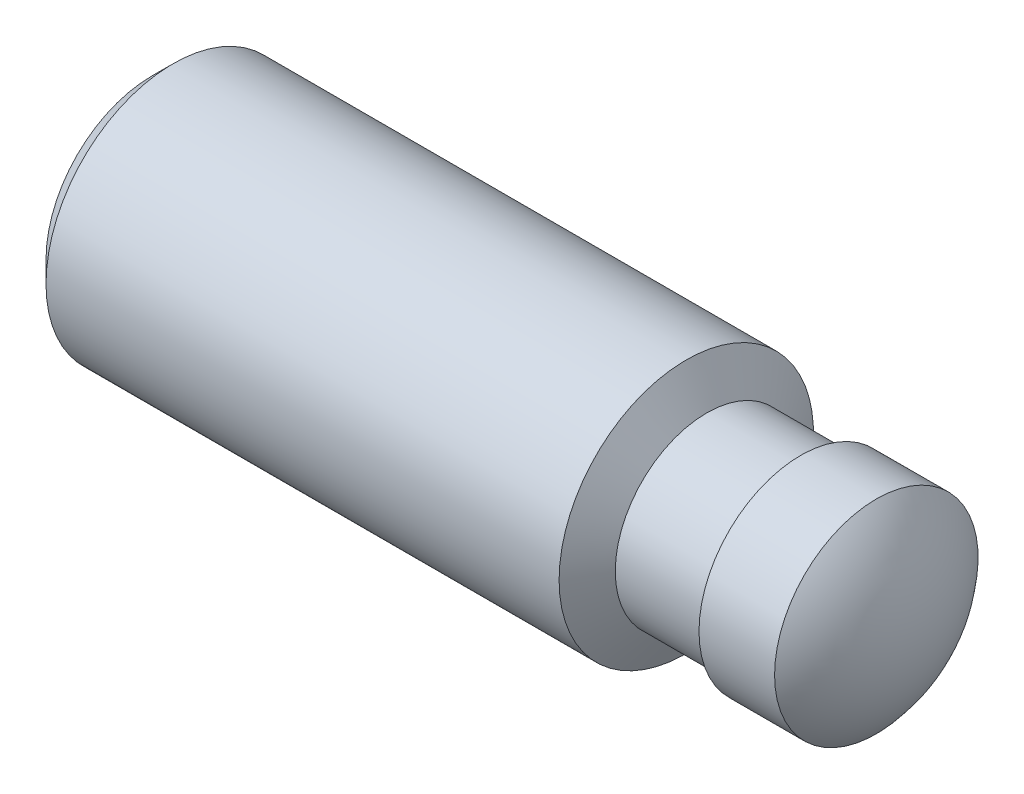
SolidWorks part; units mm, degrees
revolve "BaseBody" add sketch "BodySke" angle 360 about L5
sketch "BodySke" plane through (0, 0, 0) normal (0, 0, 1) x (1, 0, 0)
  line L0 (0.828, -5) -> (19.05, -5) construction
  line L1 (21.8083, 3.6) -> (25.5, 3.6)
  line L2 (0.828, 5) -> (21, 5)
  line L3 (21.8083, 3.6) -> (21, 5)
  line L5 (-3.175, 0) -> (33.7104, 0) construction
  line L6 (1.5, 12.7) -> (1.5, -6.35) construction
  line L7 (25.5, 3.6) -> (25.5, 4)
  line L8 (21.8083, -3.6) -> (25.5, -3.6) construction
  line L9 (0, 0) -> (0, 4.172)
  line L10 (0, 4.172) -> (0.828, 5)
  line L11 (25.5, 4) -> (28.4721, 4)
  line L12 (30, 0) -> (0, 0)
  arc A0 (28.4721, 4) -> (30, 0) centre (24, 0) cw
  dimension "oval_rad" = 6
  dimension "Diameter" = 10
  dimension "Advance" = 1.5
  dimension "Drive_ch_ang" = 45
  dimension "D1" = 60
  dimension "Minor_dia" = 8.344
  dimension "Dog_dia" = 8
  dimension "Neck_dia" = 7.2
  dimension "Thrust_len" = 4.5
  dimension "pt_len" = 9
  dimension "Length" = 30
cosmetic thread "ThreadCosmetic" [suppressed] parameters "Thread_minor"=8.344
ref_plane "Plane1" through (0, 0, 0) normal (0, 0, 1) x (1, 0, 0)
ref_plane "Plane2" through (0, 0, 0) normal (0, 1, 0) x (1, 0, 0)
ref_plane "Plane3" through (0, 0, 0) normal (1, 0, 0) x (0, 0, -1)
sketch "ThdSchSke" plane through (0, 0, 0) normal (0, 0, 1) x (1, 0, 0)
  line L0 (0.828, -4.172) -> (0.2482, -5)
  line L1 (0.828, -4.172) -> (1.4078, -5)
  line L2 (1.4078, -5) -> (1.4078, -6.25)
  line L3 (-3.175, 0) -> (5.1513, 0) construction
  line L5 (1.4078, -6.25) -> (0.2482, -6.25)
  line L6 (0.2482, -6.25) -> (0.2482, -5)
  line L7 (0.828, -5) -> (0.828, 5) construction
  dimension "Thread_minor" = 8.344
  dimension "Diameter" = 10
revolve "ThreadSchematic" [suppressed] cut sketch "ThdSchSke" angle 360 about L3
pattern_linear "ThdSchPat" [suppressed]
equation "\"Thread_minor@ThreadCosmetic\" = \"Minor_dia@BodySke\""
equation "\"Thread_minor@ThdSchSke\" = \"Thread_minor@ThreadCosmetic\""
equation "\"Diameter@ThdSchSke\" = \"Diameter@BodySke\""
equation "\"Overcut@ThdSchSke\" = \"Diameter@BodySke\" * 1.25"
equation "\"Num_threads@ThdSchPat\" = int( (\"Length@BodySke\" - ( ( ( \"Diameter@BodySke\" - \"Minor_dia@BodySke\" ) * 0.5 ) / tan( \"Drive_ch_ang@BodySke\" * 0.017453292 ) ) - \"pt_len@BodySke\" ) / \"Advance@BodySke\" + 0.999 )  + 1"
equation "\"Advance@ThdSchPat\" = (\"Length@BodySke\" - ( ( ( \"Diameter@BodySke\" - \"Minor_dia@BodySke\" ) * 0.5 ) / tan( \"Drive_ch_ang@BodySke\" * 0.017453292 ) ) - \"pt_len@BodySke\" ) /  (\"Num_threads@ThdSchPat\" - 1) 'relax it"
equation "'  \"Num_threads@ThdSchPat\" = \"Num_threads@ThdSchPat\" - sgn( \"Num_threads@ThdSchPat\" - 1) '---chamfered tips only---"
